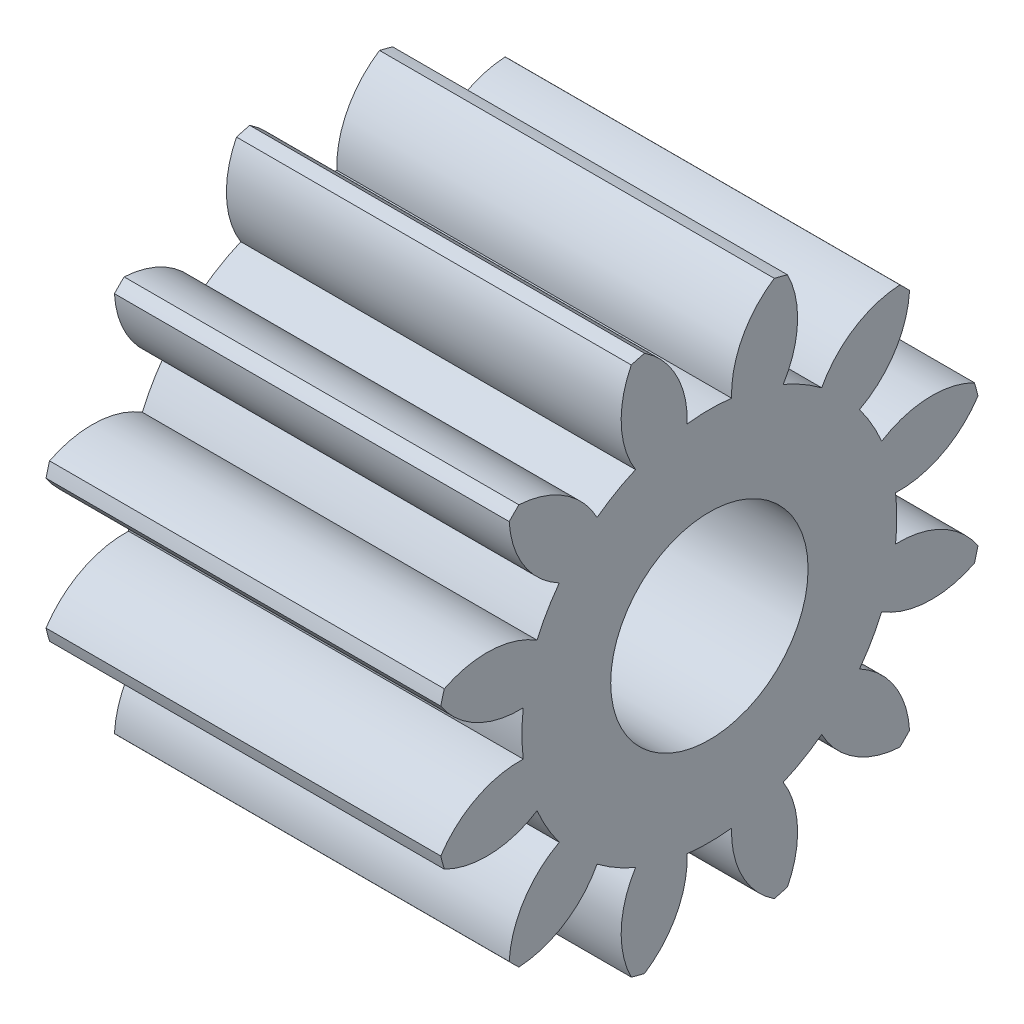
SolidWorks part; units mm, degrees
material "ABS"
ref_plane "Plane1" through (0, 0, 0) normal (0, 0, 1) x (1, 0, 0)
ref_plane "Plane2" through (0, 0, 0) normal (0, 1, 0) x (1, 0, 0)
ref_plane "Plane3" through (0, 0, 0) normal (1, 0, 0) x (0, 0, -1)
sketch "HoldingSke" plane through (0, 0, 0) normal (0, 1, 0) x (1, 0, 0)
  line L0 (0, 0) -> (0.9781, -0.2079)
  line L1 (-15, 0) -> (100, 0) construction
  line L2 (0, 0) -> (-2.1039, 2.3779)
  line L3 (0, 0) -> (-11.863, 4.5341)
  line L4 (0, 0) -> (8.4473, 1.7955)
  line L5 (0, 0) -> (-46.8476, -17.4728)
  line L6 (0, 0) -> (-8.2896, -5.593)
  line L7 (-2.1039, 2.3779) -> (8.6586, 51.2059)
  line L8 (-76.2, 54.61) -> (-75.3, 54.61)
  line L9 (-71.009, 38.7566) -> (-53.1078, 45.2721)
  line L10 (-76.2, 71.12) -> (104.1128, 71.12)
  line L11 (0, 0) -> (-10, 0)
  line L12 (-76.2, 101.6) -> (-76.162, 101.6)
  line L13 (24.9733, 27.94) -> (52.9518, 28.4284)
  line L14 (24.9733, 27.94) -> (24.9743, 27.94)
  line L15 (24.9733, 27.94) -> (100.4006, 29.5858)
  line L16 (-63.627, -1) -> (-12.827, -1)
  circle A0 centre (0, 0) radius 2.5
  circle A1 centre (0, 0) radius 4.749
  circle A2 centre (0, 0) radius 37.5
  circle A3 centre (0, 0) radius 2.5
  dimension "MHD" = 9.498
  dimension "Hub_dia" = 75
  dimension "Bore" = 5
  dimension "MBD" = 5
  dimension "Num_teeth" = 12
  dimension "Pitch" = 1
  dimension "Overall_len" = 50
  dimension "Show_teeth" = 12
  dimension "Thickness" = 10
  dimension "OAL" = 50.0001
  dimension "T_dim" = 0.9
  dimension "Ap" = 20
  dimension "H" = 19.05
  dimension "Pitch_radius" = 180.3128
  dimension "Width" = 10
  dimension "Backlash" = 0.038
  dimension "Addendum_fac" = 1
  dimension "Dedendum_fac" = 1.25
  dimension "Clearance_fac" = 0.25
  dimension "Dedendum_add" = 0.001
  dimension "Module" = 1
sketch "BasProSke" plane through (0, 0, 0) normal (0, 1, 0) x (1, 0, 0)
  line L0 (-10, 0) -> (60, 0) construction
  line L1 (0, 0) -> (0, 7)
  line L2 (0, 0) -> (10, 0)
  line L3 (10, 0) -> (10, 7)
  line L4 (10, 7) -> (0, 7)
  dimension "Thickness" = 10
  dimension "Diameter" = 14
revolve "Base-Revolve" add sketch "BasProSke" angle 360 about L0
sketch "TooCutSke" plane through (0, 0, 0) normal (1, 0, 0) x (0, 0, -1)
  line L1 (0, 0) -> (0, 107) construction
  line L2 (0, 0) -> (-0.8496, 5.9395) construction
  line L3 (0, 0) -> (-3.0836, 11.5081) construction
  line L4 (-0.8496, 5.9395) -> (-1.5418, 5.7541) construction
  arc A0 (0.5622, 4.7156) -> (-0.5622, 4.7156) centre (0, 0) ccw
  arc A1 (1.6729, 6.8233) -> (-1.6729, 6.8233) centre (0, 0) ccw
  circle A2 centre (0, 0) radius 6 construction
  circle A3 centre (0, 0) radius 5.6382 construction
  arc A4 (-0.5622, 4.7156) -> (-1.6729, 6.8233) centre (-2.9608, 4.7982) ccw
  arc A5 (1.6729, 6.8233) -> (0.5622, 4.7156) centre (2.9608, 4.7982) ccw
  dimension "Root_dia" = 9.498
  dimension "Overcut_dia" = 14.0508
  dimension "Pitch_dia" = 12
  dimension "Base_dia" = 11.2763
  dimension "Flank_rad" = 2.4
  dimension "Half_ang" = 15
  dimension "Half_CT" = 0.7167
extrude "ToothCut" cut sketch "TooCutSke" along normal through all
fillet "Breaks" [suppressed] radius 0.02
fillet "RootFillets" [suppressed] radius 0.251
pattern_circular "TeethCuts" count 12 every 30 about axis through (-10, 0, 0) along (1, 0, 0) of "ToothCut", "RootFillets", "Breaks"
sketch "HubNeaOneSke" plane through (0, 0, 0) normal (-1, 0, 0) x (0, 0, 1)
  circle A0 centre (0, 0) radius 4.749
  dimension "Diameter" = 9.498
extrude "HubNearOne" [suppressed] add sketch "HubNeaOneSke" along normal blind 40.0001
sketch "HubNeaBotSke" plane through (0, 0, 0) normal (-1, 0, 0) x (0, 0, 1)
  circle A0 centre (0, 0) radius 4.749
  dimension "Diameter" = 9.498
extrude "HubNearBoth" [suppressed] add sketch "HubNeaBotSke" along normal blind 20
ref_plane "FarPln" through (10, 0, 0) normal (1, 0, 0) x (0, 0, -1)
sketch "HubFarSke" plane through (10, 0, 0) normal (1, 0, 0) x (0, 0, -1)
  circle A0 centre (0, 0) radius 4.749
  dimension "Diameter" = 9.498
extrude "HubFar" [suppressed] add sketch "HubFarSke" along normal blind 20
sketch "BorSke" plane through (0, 0, 0) normal (1, 0, 0) x (0, 0, -1)
  circle A0 centre (0, 0) radius 2.5
  dimension "Diameter" = 5
extrude "Bore" cut sketch "BorSke" along normal mid plane 100.0001
sketch "KeySke" plane through (0, 0, 0) normal (1, 0, 0) x (0, 0, -1)
  line L0 (-1, 0) -> (-1, 3.4)
  line L1 (-1, 3.4) -> (1, 3.4)
  line L2 (1, 3.4) -> (1, 0)
  line L3 (0, 0) -> (0, 34) construction
  line L4 (-1, 0) -> (1, 0)
  dimension "Offset" = 3.4
  dimension "Width" = 2
extrude "Keyway" [suppressed] cut sketch "KeySke" along normal mid plane 100.0001
pattern_circular "Keyway2" [suppressed] count 2 every 90 about axis through (-10, 0, 0) along (1, 0, 0)
equation "' \"Module@HoldingSke\" = 6.35"
equation "' \"Num_teeth@HoldingSke\" = 12"
equation "' \"Ap@HoldingSke\" =  20"
equation "' \"Ap@HoldingSke\" = 20"
equation "' \"Width@HoldingSke\" = 0.5 * 25.4"
equation "' \"Hub_dia@HoldingSke\"= 1 * 25.4"
equation "' \"Hub_dia@HoldingSke\" = 1 * 25.4"
equation "' \"Overall_len@HoldingSke\" = 1.0 * 25.4"
equation "' \"Bore@HoldingSke\" = 0.75 * 25.4"
equation "' \"T_dim@HoldingSke\" = 0.1 * 25.4"
equation "' \"Width@KeySke\" = 0.25 * 25.4"
equation "' \"Show_teeth@HoldingSke\" = 13"
equation "' \"Backlash@HoldingSke\" = 0.009 * 25.4"
equation "' \"Addendum_fac@HoldingSke\" = 1.0"
equation "' \"Dedendum_fac@HoldingSke\" = 1.25"
equation "' \"Dedendum_add@HoldingSke\" = 0.00005 * 25.4"
equation "' \"Clearance_fac@HoldingSke\" = 0.25"
equation "\"Pitch@HoldingSke\" = 1 / \"Module@HoldingSke\""
equation "\"Overcut_dia@TooCutSke\" = (\"Num_teeth@HoldingSke\" + 2 * \"Addendum_fac@HoldingSke\") / \"Pitch@HoldingSke\" + 0.002 * 25.4"
equation "\"Pitch_dia@TooCutSke\" = \"Num_teeth@HoldingSke\" / \"Pitch@HoldingSke\""
equation "\"Base_dia@TooCutSke\" = \"Num_teeth@HoldingSke\" / \"Pitch@HoldingSke\" * cos((\"Ap@HoldingSke\"  * 3.14159265 / 180))"
equation "\"Root_dia@TooCutSke\" = (\"Num_teeth@HoldingSke\" + 2) / \"Pitch@HoldingSke\" - 2 * (\"Addendum_fac@HoldingSke\" + \"Dedendum_fac@HoldingSke\") / \"Pitch@HoldingSke\" - \"Dedendum_add@HoldingSke\" * 2"
equation "\"Half_ang@TooCutSke\" = 180 / \"Num_teeth@HoldingSke\""
equation "\"Half_CT@TooCutSke\" = \"Num_teeth@HoldingSke\" / \"Pitch@HoldingSke\" * sin((3.14159265 / 2 / \"Num_teeth@HoldingSke\")) / 2 - 7 * \"Backlash@HoldingSke\" / 4"
equation "\"Flank_rad@TooCutSke\" = \"Num_teeth@HoldingSke\" / \"Pitch@HoldingSke\" / 5"
equation "\"Radius@RootFillets\" = \"Clearance_fac@HoldingSke\" / \"Pitch@HoldingSke\" + \"Dedendum_add@HoldingSke\""
equation "\"Break_rad@Breaks\" = 0.02 / \"Pitch@HoldingSke\""
equation "\"Thickness@HoldingSke\" = \"Width@HoldingSke\""
equation "\"OAL@HoldingSke\" = \"Thickness@HoldingSke\""
equation "\"MHD@HoldingSke\" = (\"Num_teeth@HoldingSke\" + 2) / \"Pitch@HoldingSke\" - 2 * (\"Addendum_fac@HoldingSke\" + \"Dedendum_fac@HoldingSke\")  / \"Pitch@HoldingSke\" - \"Dedendum_add@HoldingSke\" * 2"
equation "\"MBD@HoldingSke\" = (\"Num_teeth@HoldingSke\" + 2) / \"Pitch@HoldingSke\" - 2 * (\"Addendum_fac@HoldingSke\" + \"Dedendum_fac@HoldingSke\")  / \"Pitch@HoldingSke\" - \"Dedendum_add@HoldingSke\" * 2 - 0.002 * 25.4"
equation "\"MHD@HoldingSke\" = ((sgn( \"MHD@HoldingSke\" - \"Hub_dia@HoldingSke\" )-1)*( \"MHD@HoldingSke\" - \"Hub_dia@HoldingSke\" ))/-2+ \"Hub_dia@HoldingSke\""
equation "\"MBD@HoldingSke\" = ((sgn( \"MBD@HoldingSke\" - \"Bore@HoldingSke\" )-1)*( \"MBD@HoldingSke\" - \"Bore@HoldingSke\" ))/-2+ \"Bore@HoldingSke\""
equation "\"OAL@HoldingSke\" = ((sgn( \"OAL@HoldingSke\" - \"Overall_len@HoldingSke\" )+1)*( \"OAL@HoldingSke\" - \"Overall_len@HoldingSke\" ))/2 + \"Overall_len@HoldingSke\" + 0.000002 * 25.4"
equation "\"Num_teeth@TeethCuts\" = int( \"Show_teeth@HoldingSke\" ) + 1"
equation "\"Num_teeth@TeethCuts\" = ((sgn( \"Num_teeth@TeethCuts\" - \"Num_teeth@HoldingSke\" )-1)*( \"Num_teeth@TeethCuts\" - \"Num_teeth@HoldingSke\" ))/-2+ \"Num_teeth@HoldingSke\""
equation "\"Num_teeth@TeethCuts\" = ((sgn( \"Num_teeth@TeethCuts\" - 2.0)+1)*( \"Num_teeth@TeethCuts\" - 2.0))/2 +2.0"
equation "\"Angle@TeethCuts\" = 360.0 / \"Num_teeth@HoldingSke\""
equation "\"Diameter@BasProSke\" = (\"Num_teeth@HoldingSke\" + 2 * \"Addendum_fac@HoldingSke\") / \"Pitch@HoldingSke\""
equation "\"Thickness@BasProSke\"  = \"Thickness@HoldingSke\""
equation "' \"Fillet_rad@BasProSke\" =  \"Thickness@HoldingSke\" * 0.05"
equation "' \"Fillet_rad@BasProSke\" = \"Thickness@HoldingSke\" * 0.05"
equation "\"MHD@HoldingSke\" = ((sgn( \"MHD@HoldingSke\" - \"Root_dia@TooCutSke\" )-1)*( \"MHD@HoldingSke\" - \"Root_dia@TooCutSke\" ))/-2+ \"Root_dia@TooCutSke\""
equation "\"Diameter@HubNeaOneSke\" = \"MHD@HoldingSke\""
equation "\"Length@HubNearOne\" = \"OAL@HoldingSke\" - \"Thickness@BasProSke\""
equation "\"Diameter@HubNeaBotSke\" = \"MHD@HoldingSke\""
equation "\"Length@HubNearBoth\" = ( \"OAL@HoldingSke\" - \"Thickness@BasProSke\" ) / 2.0"
equation "\"Thickness@FarPln\" = \"Thickness@BasProSke\""
equation "\"Diameter@HubFarSke\" = \"MHD@HoldingSke\""
equation "\"Length@HubFar\" = ( \"OAL@HoldingSke\" - \"Thickness@BasProSke\" ) / 2.0"
equation "\"Diameter@BorSke\" = \"MBD@HoldingSke\""
equation "\"D1@Bore\" = \"OAL@HoldingSke\" * 2.0"
equation "\"D1@Keyway\" = \"OAL@HoldingSke\" * 2.0"
equation "\"Offset@KeySke\" = \"T_dim@HoldingSke\" + \"MBD@HoldingSke\" / 2.0"
